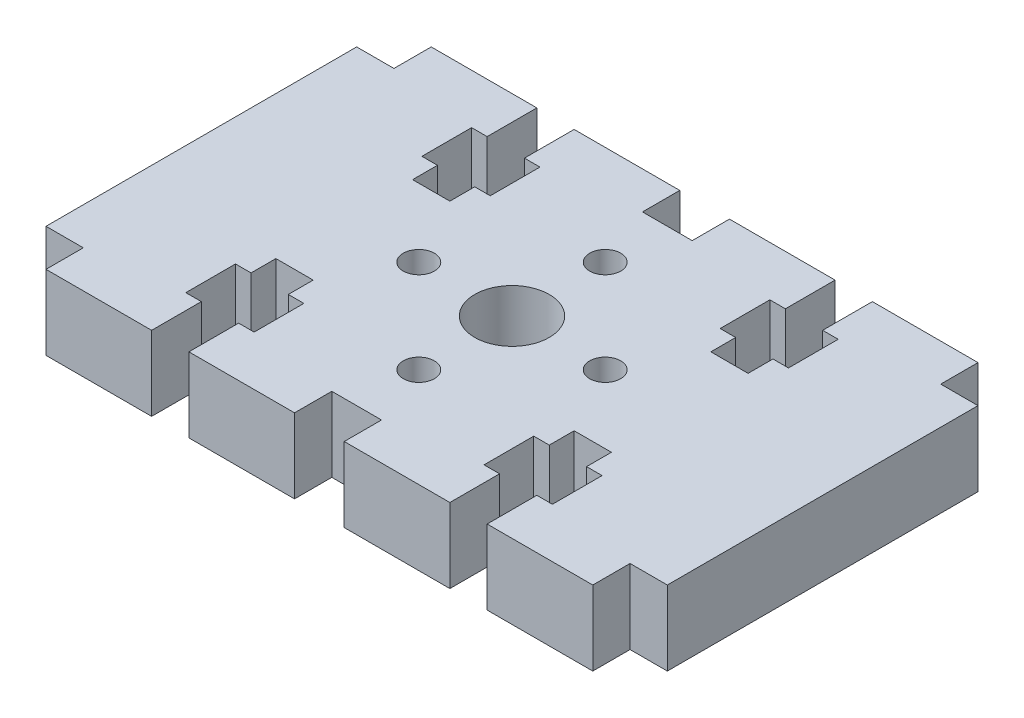
SolidWorks part; units mm, degrees
ref_plane "前视基准面" through (0, 0, 0) normal (0, 0, 1) x (1, 0, 0)
ref_plane "上视基准面" through (0, 0, 0) normal (0, 1, 0) x (1, 0, 0)
ref_plane "右视基准面" through (0, 0, 0) normal (1, 0, 0) x (0, 0, -1)
other "Configuration Table"
sketch "草图1" plane through (0, 0, 0) normal (0, 1, 0) x (1, 0, 0)
  line L0 (25, -25) -> (25, -12.5)
  line L1 (0, 0) -> (50, 0)
  line L2 (0, 0) -> (0, -25)
  line L3 (0, -25) -> (50, -25)
  line L4 (50, 0) -> (50, -25)
  line L5 (3, -25) -> (23, -25)
  line L6 (3, -25) -> (3, -28)
  line L7 (3, -28) -> (23, -28)
  line L8 (23, -25) -> (23, -28)
  line L9 (11.5, -18) -> (14.5, -18)
  line L10 (11.5, -18) -> (11.5, -38)
  line L11 (11.5, -38) -> (14.5, -38)
  line L12 (14.5, -18) -> (14.5, -38)
  line L13 (11.5, -18) -> (14.5, -38) construction
  line L14 (11.5, -38) -> (14.5, -18) construction
  line L15 (10.25, -20) -> (15.75, -20)
  line L16 (10.25, -20) -> (10.25, -24)
  line L17 (10.25, -24) -> (15.75, -24)
  line L18 (15.75, -20) -> (15.75, -24)
  line L19 (10.25, -20) -> (15.75, -24) construction
  line L20 (10.25, -24) -> (15.75, -20) construction
  line L21 (38.5, -38) -> (35.5, -38)
  line L22 (35.5, -18) -> (35.5, -38)
  line L23 (38.5, -18) -> (35.5, -18)
  line L24 (38.5, -18) -> (38.5, -38)
  line L25 (39.75, -24) -> (34.25, -24)
  line L26 (34.25, -20) -> (34.25, -24)
  line L27 (39.75, -20) -> (34.25, -20)
  line L28 (39.75, -20) -> (39.75, -24)
  line L29 (47, -28) -> (27, -28)
  line L30 (27, -25) -> (27, -28)
  line L31 (47, -25) -> (27, -25)
  line L32 (47, -25) -> (47, -28)
  line L33 (0, -12.5) -> (50, -12.5)
  line L34 (10.25, -1) -> (15.75, -1)
  line L35 (15.75, -5) -> (15.75, -1)
  line L36 (10.25, -5) -> (15.75, -5)
  line L37 (10.25, -5) -> (10.25, -1)
  line L38 (11.5, 13) -> (14.5, 13)
  line L39 (14.5, -7) -> (14.5, 13)
  line L40 (11.5, -7) -> (14.5, -7)
  line L41 (11.5, -7) -> (11.5, 13)
  line L42 (39.75, -5) -> (39.75, -1)
  line L43 (39.75, -5) -> (34.25, -5)
  line L44 (34.25, -5) -> (34.25, -1)
  line L45 (39.75, -1) -> (34.25, -1)
  line L46 (38.5, -7) -> (38.5, 13)
  line L47 (38.5, -7) -> (35.5, -7)
  line L48 (35.5, -7) -> (35.5, 13)
  line L49 (38.5, 13) -> (35.5, 13)
  line L50 (47, 0) -> (47, 3)
  line L51 (47, 0) -> (27, 0)
  line L52 (27, 0) -> (27, 3)
  line L53 (47, 3) -> (27, 3)
  line L54 (3, 3) -> (23, 3)
  line L55 (23, 0) -> (23, 3)
  line L56 (3, 0) -> (23, 0)
  line L57 (3, 0) -> (3, 3)
  circle A0 centre (25, -12.5) radius 10.4
  circle A1 centre (17.5, -12.5) radius 1.25
  circle A3 centre (25, -12.5) radius 3
  circle A4 centre (25, -5) radius 1.25
  circle A5 centre (32.5, -12.5) radius 1.25
  circle A6 centre (25, -20) radius 1.25
  point P15 (13, -28)
  point P20 (13, -22)
  dimension "D3" = 20.8
  dimension "D4" = 2.5
  dimension "D13" = 6
  dimension "D14" = 7.5
  dimension "D1" = 50
  dimension "D2" = 25
  dimension "D6" = 20
  dimension "D7" = 3
  dimension "D8" = 3
  dimension "D9" = 3
  dimension "D10" = 20
  dimension "D11" = 5.5
  dimension "D12" = 4
  dimension "D5" = 4
extrude "凸台-拉伸1" add sketch "草图1" along normal blind 6
